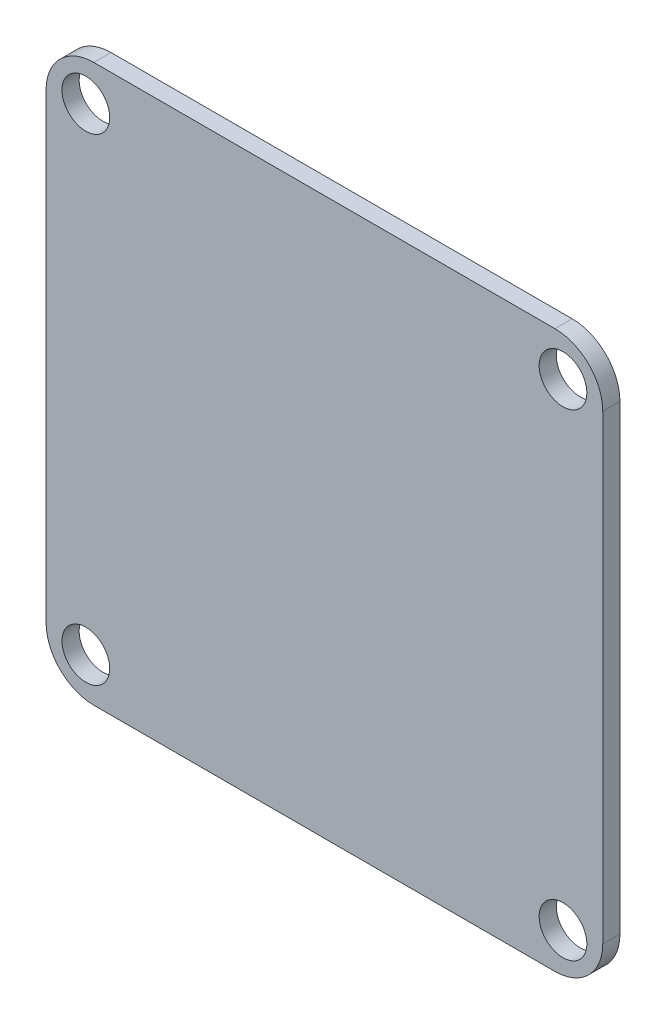
SolidWorks part; units mm, degrees
ref_plane "Front Plane" through (0, 0, 0) normal (0, 0, 1) x (1, 0, 0)
ref_plane "Top Plane" through (0, 0, 0) normal (0, 1, 0) x (1, 0, 0)
ref_plane "Right Plane" through (0, 0, 0) normal (1, 0, 0) x (0, 0, -1)
sketch "Sketch1" plane through (0, 0, 0) normal (0, 0, 1) x (1, 0, 0)
  line L0 (0, 0) -> (0, 50000) construction
  line L1 (-14.5, -17.5) -> (14.5, -17.5)
  line L2 (-17.5, -14.5) -> (-17.5, 14.5)
  line L3 (-14.5, 17.5) -> (14.5, 17.5)
  line L4 (17.5, -14.5) -> (17.5, 14.5)
  line L5 (-17.5, -17.5) -> (17.5, 17.5) construction
  line L6 (-17.5, 17.5) -> (17.5, -17.5) construction
  line L7 (0, 0) -> (-50000, 0) construction
  circle A0 centre (-15, -15) radius 1.5
  circle A1 centre (15, -15) radius 1.5
  circle A2 centre (15, 15) radius 1.5
  circle A3 centre (-15, 15) radius 1.5
  arc A4 (14.5, -17.5) -> (17.5, -14.5) centre (14.5, -14.5) ccw
  arc A5 (14.5, 17.5) -> (17.5, 14.5) centre (14.5, 14.5) cw
  arc A6 (-17.5, 14.5) -> (-14.5, 17.5) centre (-14.5, 14.5) cw
  arc A7 (-14.5, -17.5) -> (-17.5, -14.5) centre (-14.5, -14.5) cw
  point P0 (0, 0)
  dimension "D3" = 3
  dimension "D5" = 3
  dimension "D1" = 35
  dimension "D2" = 35
  dimension "D4" = 15
extrude "Boss-Extrude1" add sketch "Sketch1" along normal blind 1.08
